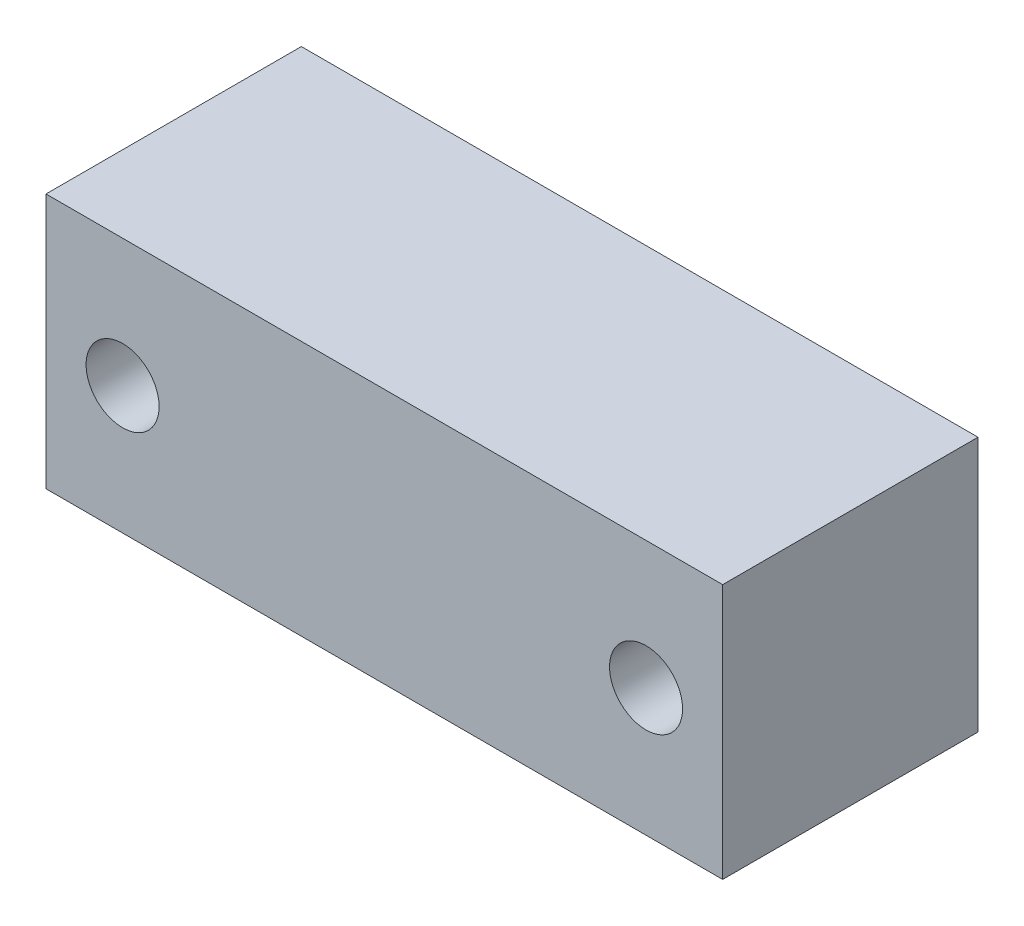
SolidWorks part; units mm, degrees
ref_plane "정면" through (0, 0, 0) normal (0, 0, 1) x (1, 0, 0)
ref_plane "윗면" through (0, 0, 0) normal (0, 1, 0) x (1, 0, 0)
ref_plane "우측면" through (0, 0, 0) normal (1, 0, 0) x (0, 0, -1)
sketch "스케치1" plane through (0, 0, 0) normal (0, 0, 1) x (1, 0, 0)
  line L1 (-26.5, 10) -> (26.5, 10)
  line L2 (-26.5, 10) -> (-26.5, -10)
  line L3 (-26.5, -10) -> (26.5, -10)
  line L4 (26.5, 10) -> (26.5, -10)
  line L5 (-26.5, 10) -> (26.5, -10) construction
  line L6 (-26.5, -10) -> (26.5, 10) construction
  point P0 (0, 0)
  dimension "D1" = 20
  dimension "D2" = 53
extrude "보스-돌출1" add sketch "스케치1" along normal blind 20
hole_wizard "M4 여유 구멍1" positions "스케치2" profile "스케치3" hole size "M4" standard "KS" end condition through all
sketch "스케치2" plane through (0, 0, 20) normal (0, 0, 1) x (1, 0, 0)
  line L0 (26.5, 10) -> (-26.5, 10) construction
  point P0 (-20.5, 0)
  point P1 (20.5, 0)
  dimension "D1" = 10
  dimension "D2" = 20.5
  dimension "D3" = 0
  dimension "D4" = 20.5
sketch "스케치3" plane through (-20.5, 0, 20) normal (1, 0, 0) x (0, -1, 0)
  line L0 (0, 0) -> (0, 20)
  line L1 (0, 20) -> (2.86, 20)
  line L2 (2.86, 20) -> (2.86, 0)
  line L5 (2.86, 0) -> (0, 0)
  line L11 (0, -6.35) -> (0, 107.95) construction
  dimension "관통 구멍 지름" = 5.72
  dimension "관통 구멍 깊이" = 20
